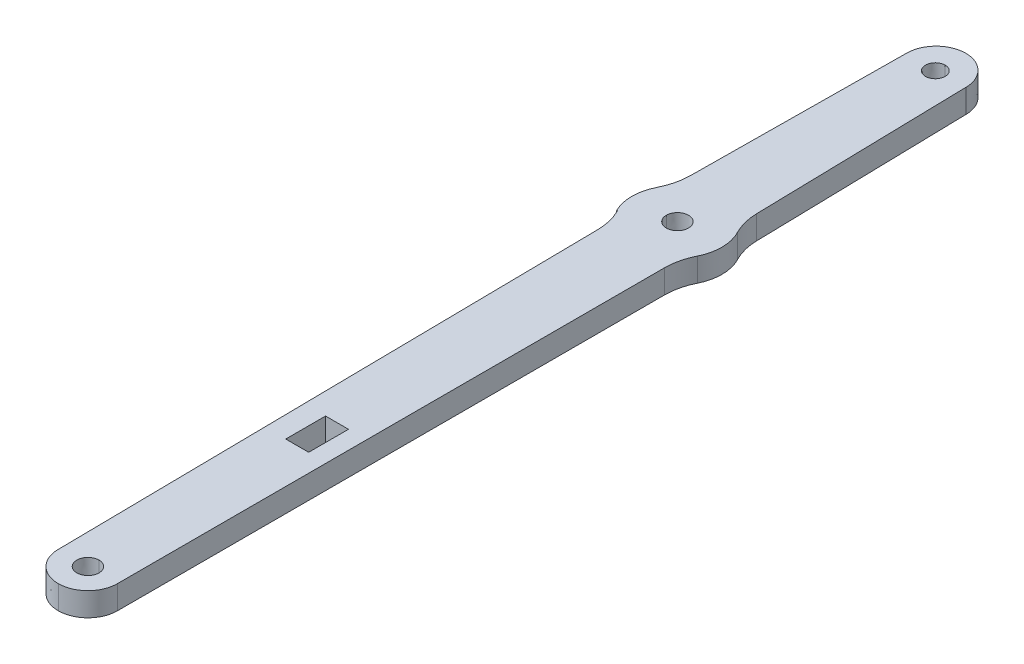
SolidWorks part; units mm, degrees
material "Acrylic (Medium-high impact)"
ref_plane "Front Plane" through (0, 0, 0) normal (0, 0, 1) x (1, 0, 0)
ref_plane "Top Plane" through (0, 0, 0) normal (0, 1, 0) x (1, 0, 0)
ref_plane "Right Plane" through (0, 0, 0) normal (1, 0, 0) x (0, 0, -1)
sketch "Sketch1" plane through (0, 0, 0) normal (0, 1, 0) x (1, 0, 0)
  line L0 (11.672, 52.5233) -> (11.672, 52.4234)
  line L1 (11.672, 52.4234) -> (12.324, 23.612)
  line L2 (12.4276, 11.079) -> (12.4276, -62.6692)
  line L3 (4.4422, -62.7218) -> (3.4742, 11.02)
  line L4 (2.5865, 14.5818) -> (2.5233, 14.5243)
  line L5 (2.551, 19.9734) -> (2.5604, 20.0309)
  line L6 (3.4134, 23.5532) -> (3.6872, 52.3707)
  line L7 (3.6872, 52.3707) -> (3.6872, 52.4707)
  line L200 (9.9818, -34.4577) -> (9.9818, -29.0842)
  line L201 (9.9818, -29.0842) -> (6.8877, -29.0842)
  line L202 (6.8877, -29.0842) -> (6.8877, -34.4577)
  line L203 (6.8877, -34.4577) -> (9.9818, -34.4577)
  spline S0 degree 3 poles (6.4125, 17.3322) (6.4123, 18.1607) (7.0827, 18.8322) (7.9096, 18.8322) (8.7367, 18.8322) (9.4069, 18.1607) (9.4069, 17.3322) (9.4069, 16.5038) (8.7367, 15.8321) (7.9098, 15.8321) knots 1 1 1 1 2 2 2 3 3 3 4 4 4 4
  spline S1 degree 3 poles (7.9098, 15.8321) (7.0827, 15.8321) (6.4125, 16.5038) (6.4125, 17.3322) knots 0 0 0 0 1 1 1 1
  spline S2 degree 3 poles (7.6799, 53.6577) (8.4103, 53.6577) (9.0028, 53.0643) (9.0028, 52.3327) (9.0028, 51.601) (8.4103, 51.0077) (7.6799, 51.0077) knots 2 2 2 2 3 3 3 4 4 4 4
  spline S3 degree 3 poles (7.6799, 51.0077) (6.9494, 51.0077) (6.3574, 51.601) (6.3574, 52.3327) (6.3574, 53.0643) (6.9494, 53.6577) (7.6799, 53.6577) knots 0 0 0 0 1 1 1 2 2 2 2
  spline S4 degree 3 poles (8.4346, -61.1691) (9.2617, -61.169) (9.9322, -61.8406) (9.9322, -62.669) (9.9322, -63.4976) (9.2617, -64.1691) (8.4348, -64.1691) knots 2 2 2 2 3 3 3 4 4 4 4
  spline S5 degree 3 poles (8.4348, -64.1691) (7.6077, -64.1692) (6.9373, -63.4976) (6.9373, -62.6692) (6.9373, -61.8406) (7.6077, -61.1691) (8.4346, -61.1691) knots 0 0 0 0 1 1 1 2 2 2 2
  spline S6 degree 3 poles (12.324, 23.612) (12.3517, 22.3882) (12.6592, 21.1871) (13.2233, 20.1013) knots 2 2 2 2 3 3 3 3
  spline S7 degree 3 poles (13.2233, 20.1013) (14.1082, 18.3969) (14.125, 16.3711) (13.2684, 14.6522) knots 3 3 3 3 4 4 4 4
  spline S8 degree 3 poles (13.2684, 14.6522) (12.7155, 13.5424) (12.4276, 12.3192) (12.4276, 11.079) knots 4 4 4 4 5 5 5 5
  spline S9 degree 3 poles (12.4276, -62.6692) (12.4276, -64.868) (10.656, -66.6546) (8.4611, -66.6692) knots 6 6 6 6 7 7 7 7
  spline S10 degree 3 poles (8.4611, -66.6692) (6.2659, -66.6835) (4.471, -64.9206) (4.4422, -62.7218) knots 7 7 7 7 8 8 8 8
  spline S11 degree 3 poles (3.4742, 11.02) (3.4579, 12.2601) (3.1539, 13.4797) (2.5865, 14.5818) knots 9 9 9 9 10 10 10 10
  spline S12 degree 3 poles (2.5233, 14.5243) (1.6611, 16.2404) (1.6714, 18.2663) (2.551, 19.9734) knots 11 11 11 11 12 12 12 12
  spline S13 degree 3 poles (2.5604, 20.0309) (3.1099, 21.1242) (3.4017, 22.3292) (3.4134, 23.5532) knots 13 13 13 13 14 14 14 14
  spline S14 degree 3 poles (3.6872, 52.4707) (3.7079, 54.6548) (5.4734, 56.4183) (7.6537, 56.4328) knots 16 16 16 16 17 17 17 17
  spline S15 degree 3 poles (7.6537, 56.4328) (9.8338, 56.4471) (11.6224, 54.7068) (11.672, 52.5233) knots 17 17 17 17 18 18 18 18
extrude "Boss-Extrude1" add sketch "Sketch1" along normal blind 3.175
